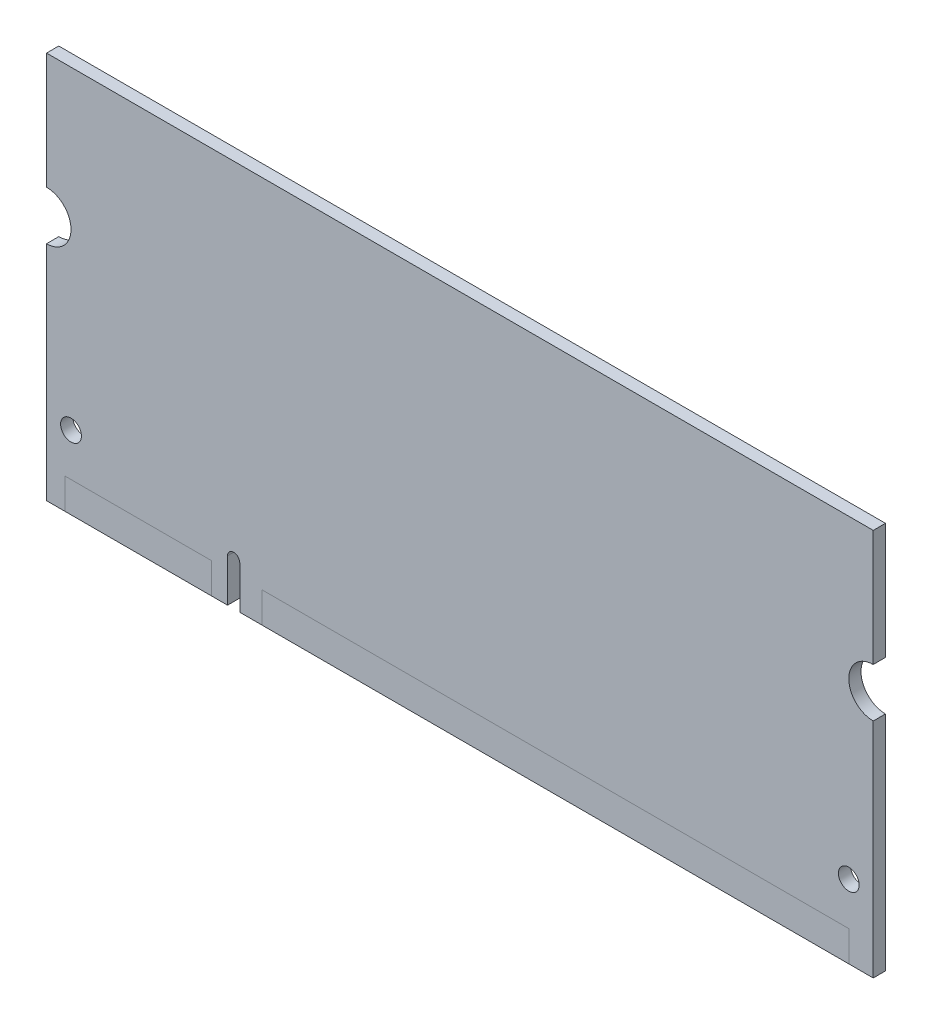
SolidWorks part; units mm, degrees
ref_plane "Front Plane" through (0, 0, 0) normal (0, 0, 1) x (1, 0, 0)
ref_plane "Top Plane" through (0, 0, 0) normal (0, 1, 0) x (1, 0, 0)
ref_plane "Right Plane" through (0, 0, 0) normal (1, 0, 0) x (0, 0, -1)
sketch "Sketch1" plane through (0, 0, 0) normal (0, 0, 1) x (1, 0, 0)
  line L0 (33.8, 15.85) -> (-33.8, -15.85) construction
  line L1 (-33.8, 15.85) -> (33.8, 15.85)
  line L2 (-33.8, 15.85) -> (-33.8, -15.85)
  line L3 (-33.8, -15.85) -> (33.8, -15.85)
  line L4 (33.8, 15.85) -> (33.8, -15.85)
  dimension "D1" = 67.6
  dimension "D2" = 31.7
extrude "MAIN BOARD" add sketch "Sketch1" along normal mid plane 1
sketch "Sketch2" plane through (0, 0, 0.5) normal (0, 0, 1) x (1, 0, 0)
  line L0 (-33.8, 15.85) -> (-33.8, -15.85) construction
  line L1 (-33.8, 6.35) -> (-33.8, 2.35)
  line L2 (33.8, 15.85) -> (-33.8, 15.85) construction
  line L3 (0, -1000) -> (0, 49000) construction
  line L4 (33.8, 6.35) -> (33.8, 2.35)
  arc A0 (-33.8, 6.35) -> (-33.8, 2.35) centre (-33.8, 4.35) cw
  arc A1 (33.8, 6.35) -> (33.8, 2.35) centre (33.8, 4.35) ccw
  dimension "D1" = 9.5
  dimension "D2" = 4
  dimension "D3" = 2
extrude "MOUNTING CLIP GROOVES" cut sketch "Sketch2" against normal through all
hole_wizard "M1.7 (1.7) LOCATING PIN HOLES" positions "Sketch4" profile "Sketch3" hole size "M1.7" standard "Ansi Metric" end condition through all
sketch "Sketch4" plane through (0, 0, 0.5) normal (0, 0, 1) x (1, 0, 0)
  line L0 (0, -1000) -> (0, 49000) construction
  line L1 (-33.8, 2.35) -> (-33.8, -15.85) construction
  line L2 (-33.8, -15.85) -> (33.8, -15.85) construction
  point P1 (31.8, -9.85)
  point P5 (-31.8, -9.85)
  dimension "D1" = 2
  dimension "D2" = 6
sketch "Sketch3" plane through (-31.8, -9.85, 0.5) normal (1, 0, 0) x (0, -1, 0)
  line L0 (0, 0) -> (0, 1)
  line L1 (0, 1) -> (0.85, 1)
  line L2 (0.85, 1) -> (0.85, 0)
  line L5 (0.85, 0) -> (0, 0)
  line L11 (0, -6.35) -> (0, 107.95) construction
  dimension "Thru Hole Dia." = 1.7
  dimension "Thru Hole Depth" = 1
sketch "Sketch5" plane through (0, 0, 0.5) normal (0, 0, 1) x (1, 0, 0)
  line L0 (-19, -15.85) -> (-19, -12.35)
  line L1 (-33.8, -15.85) -> (33.8, -15.85) construction
  line L2 (-18, -12.35) -> (-18, -15.85)
  line L3 (-18, -15.85) -> (-19, -15.85)
  line L4 (-33.8, 2.35) -> (-33.8, -15.85) construction
  arc A0 (-19, -12.35) -> (-18, -12.35) centre (-18.5, -12.35) cw
  dimension "D3" = 4
  dimension "D1" = 14.8
  dimension "D2" = 1
extrude "LOCATING SLOT" cut sketch "Sketch5" against normal through all
sketch "Sketch7" plane through (0, 0, 0.5) normal (0, 0, 1) x (1, 0, 0)
  line L0 (-33.8, -15.85) -> (-19, -15.85) construction
  line L1 (-32.3, -15.85) -> (-20.3, -15.85)
  line L2 (-32.3, -15.85) -> (-32.3, -13.35)
  line L3 (-32.3, -13.35) -> (-20.3, -13.35)
  line L4 (-20.3, -15.85) -> (-20.3, -13.35)
  line L5 (-33.8, 2.35) -> (-33.8, -15.85) construction
  dimension "D1" = 12
  dimension "D2" = 2.5
  dimension "D3" = 1.5
split line "Split Line1"
sketch "Sketch8" plane through (0, 0, 0.5) normal (0, 0, 1) x (1, 0, 0)
  line L0 (-18, -15.85) -> (33.8, -15.85) construction
  line L1 (-16.2, -15.85) -> (31.8, -15.85)
  line L2 (-16.2, -15.85) -> (-16.2, -13.35)
  line L3 (-16.2, -13.35) -> (31.8, -13.35)
  line L4 (31.8, -15.85) -> (31.8, -13.35)
  line L5 (-32.3, -13.35) -> (-20.3, -13.35) construction
  line L6 (33.8, -15.85) -> (33.8, 2.35) construction
  dimension "D1" = 48
  dimension "D2" = 2
split line "Split Line2"
